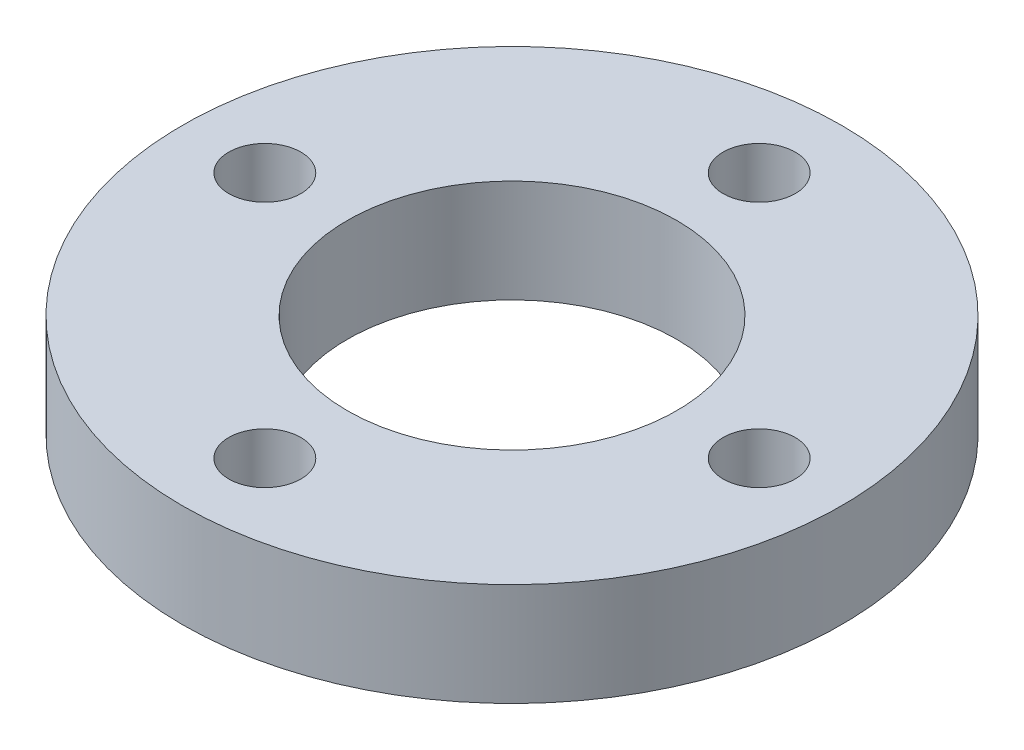
SolidWorks part; units mm, degrees
ref_plane "前视基准面" through (0, 0, 0) normal (0, 0, 1) x (1, 0, 0)
ref_plane "上视基准面" through (0, 0, 0) normal (0, 1, 0) x (1, 0, 0)
ref_plane "右视基准面" through (0, 0, 0) normal (1, 0, 0) x (0, 0, -1)
sketch "草图1" plane through (0, 0, 0) normal (0, 1, 0) x (1, 0, 0)
  circle A0 centre (0, 0) radius 16
  circle A1 centre (0, 0) radius 12 construction
  circle A2 centre (0, 0) radius 8
  circle A3 centre (12, 0) radius 1.75
  circle A4 centre (0, -12) radius 1.75
  circle A5 centre (-12, 0) radius 1.75
  circle A6 centre (0, 12) radius 1.75
  point P16 (0, 0)
  dimension "D1" = 32
  dimension "D2" = 24
  dimension "D3" = 3.5
  dimension "D4" = 16
  dimension "D5" = 4
extrude "凸台-拉伸1" add sketch "草图1" along normal blind 5
